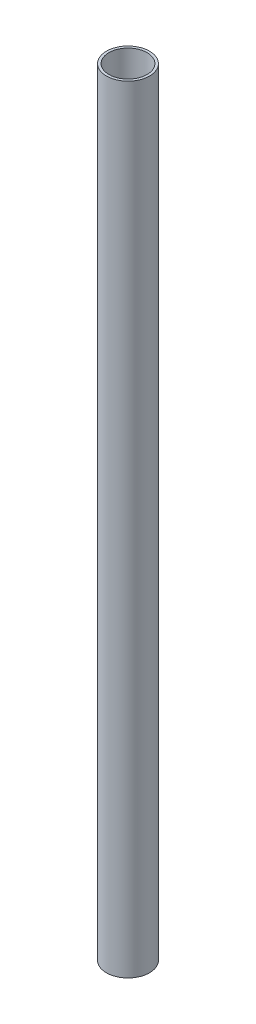
SolidWorks part; units mm, degrees
material "AISI 4340 Steel, annealed"
ref_plane "X-Y Datum" through (0, 0, 0) normal (0, 0, 1) x (1, 0, 0)
ref_plane "X-Z Datum" through (0, 0, 0) normal (0, 1, 0) x (1, 0, 0)
ref_plane "Y-Z Datum" through (0, 0, 0) normal (1, 0, 0) x (0, 0, -1)
ref_plane "Plane1" through (163.0475, 166.552, 0) normal (0, 1, 0) x (1, 0, 0)
sketch "Sketch1" plane through (163.0475, 166.552, 0) normal (0, 1, 0) x (1, 0, 0)
  circle A0 centre (0, 0) radius 6.35
  circle A1 centre (0, 0) radius 5.6134
  dimension "D1" = 12.7
  dimension "D2" = 11.2268
extrude "Boss-Extrude1" add sketch "Sketch1" against normal up to surface (114.4399 mm away) and the other way up to surface (114.4399 mm away)
